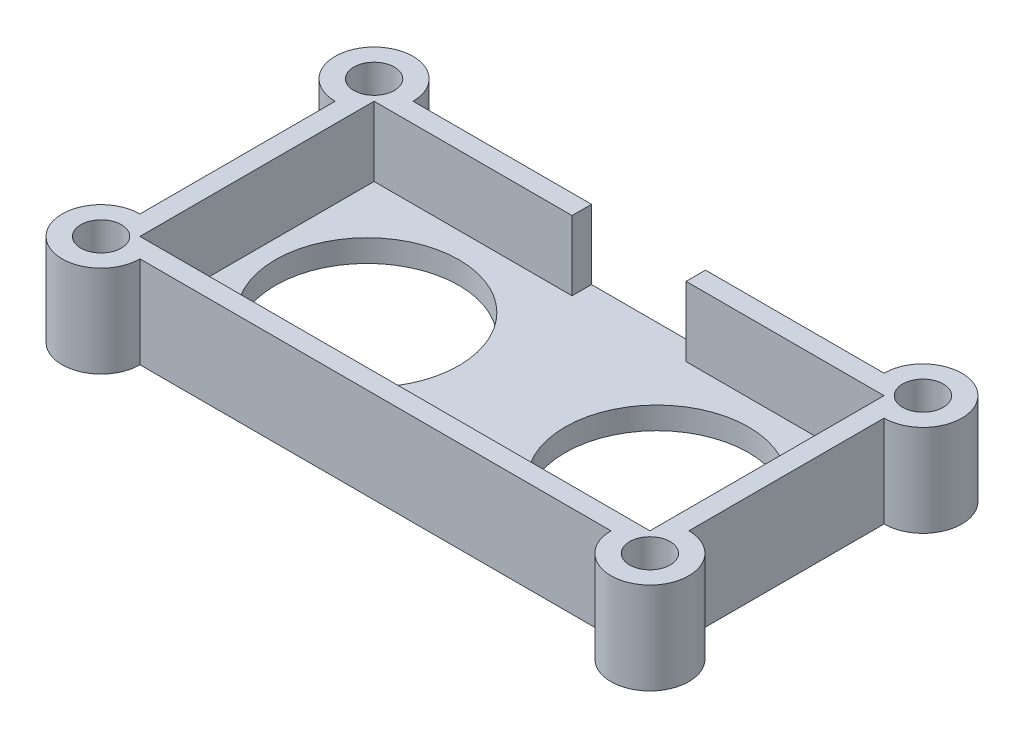
SolidWorks part; units mm, degrees
ref_plane "Front Plane" through (0, 0, 0) normal (0, 0, 1) x (1, 0, 0)
ref_plane "Top Plane" through (0, 0, 0) normal (0, 1, 0) x (1, 0, 0)
ref_plane "Right Plane" through (0, 0, 0) normal (1, 0, 0) x (0, 0, -1)
sketch "Sketch1" plane through (0, 0, 0) normal (0, 1, 0) x (1, 0, 0)
  line L1 (-24.675, 12.275) -> (24.675, 12.275)
  line L2 (-24.675, 12.275) -> (-24.675, -12.275)
  line L3 (-24.675, -12.275) -> (24.675, -12.275)
  line L4 (24.675, 12.275) -> (24.675, -12.275)
  dimension "D1" = 49.35
  dimension "D2" = 24.675
  dimension "D3" = 24.55
  dimension "D4" = 12.275
extrude "Boss-Extrude1" add sketch "Sketch1" along normal blind 2
sketch "Sketch2" plane through (0, 2, 0) normal (0, 1, 0) x (1, 0, 0)
  line L0 (-24.675, 12.275) -> (-24.675, -12.275)
  line L1 (-24.675, -12.275) -> (24.675, -12.275)
  line L2 (24.675, -12.275) -> (24.675, 12.275)
  line L3 (24.675, 12.275) -> (5.125, 12.275)
  line L4 (24.675, 12.275) -> (-24.675, 12.275) construction
  line L5 (5.125, 12.275) -> (5.125, 10.525)
  line L6 (5.125, 10.525) -> (22.925, 10.525)
  line L7 (22.925, 10.525) -> (22.925, -10.525)
  line L8 (22.925, -10.525) -> (-22.925, -10.525)
  line L9 (-22.925, -10.525) -> (-22.925, 10.525)
  line L10 (-22.925, 10.525) -> (-5.125, 10.525)
  line L11 (-5.125, 10.525) -> (-5.125, 12.275)
  line L12 (-5.125, 12.275) -> (-24.675, 12.275)
  dimension "D1" = 19.55
  dimension "D2" = 1.75
  dimension "D3" = 1.75
  dimension "D4" = 1.75
  dimension "D5" = 1.75
  dimension "D6" = 1.75
  dimension "D7" = 19.55
extrude "Boss-Extrude2" add sketch "Sketch2" along normal blind 6.25
sketch "Sketch4" plane through (0, 2, 0) normal (0, 1, 0) x (1, 0, 0)
  line L0 (-24.675, 12.275) -> (-24.675, 8.775)
  line L1 (-24.675, 12.275) -> (-21.175, 12.275)
  line L2 (-24.675, -12.275) -> (-24.675, -8.775)
  line L3 (-24.675, -12.275) -> (-21.175, -12.275)
  line L4 (24.675, -12.275) -> (21.175, -12.275)
  line L5 (24.675, -12.275) -> (24.675, -8.775)
  line L6 (24.675, 8.775) -> (24.675, 12.275)
  line L7 (24.675, 12.275) -> (21.175, 12.275)
  arc A0 (-21.175, 12.275) -> (-24.675, 8.775) centre (-24.675, 12.275) ccw
  arc A1 (-24.675, -8.775) -> (-21.175, -12.275) centre (-24.675, -12.275) ccw
  arc A2 (21.175, -12.275) -> (24.675, -8.775) centre (24.675, -12.275) ccw
  arc A3 (24.675, 8.775) -> (21.175, 12.275) centre (24.675, 12.275) ccw
  dimension "D1" = 7
  dimension "D2" = 7
  dimension "D3" = 7
  dimension "D4" = 7
extrude "Boss-Extrude3" add sketch "Sketch4" along normal up to surface and the other way up to surface
sketch "Sketch3" plane through (0, 2, 0) normal (0, 1, 0) x (1, 0, 0)
  line L0 (-3, -7.35) -> (3.25, -7.35) construction
  line L1 (-3, -4.975) -> (3.25, -4.975)
  line L2 (-3, -9.725) -> (3.25, -9.725)
  line L5 (-22.925, -10.525) -> (-22.925, 10.525) construction
  line L7 (22.925, 10.525) -> (22.925, -10.525) construction
  line L9 (22.925, -10.525) -> (-22.925, -10.525) construction
  line L11 (22.925, -10.525) -> (-22.925, -10.525) construction
  line L12 (-22.925, -10.525) -> (-22.925, 10.525) construction
  circle A0 centre (-13.025, 0) radius 8.25
  circle A1 centre (13.025, 0) radius 8.25
  arc A2 (-3, -4.975) -> (-3, -9.725) centre (-3, -7.35) ccw
  arc A3 (3.25, -9.725) -> (3.25, -4.975) centre (3.25, -7.35) ccw
  circle A4 centre (-24.675, 12.275) radius 1.825
  circle A5 centre (-24.675, -12.275) radius 1.825
  circle A6 centre (24.675, 12.275) radius 1.825
  circle A7 centre (24.675, -12.275) radius 1.825
  point P6 (0.125, -7.35)
  point P16 (-22.925, 0)
  point P18 (22.925, 0)
  point P23 (-5.375, -7.35)
  point P24 (5.625, -7.35)
  dimension "D1" = 16.5
  dimension "D2" = 16.5
  dimension "D11" = 3.65
  dimension "D12" = 3.65
  dimension "D13" = 3.65
  dimension "D14" = 3.65
  dimension "D3" = 9.9
  dimension "D4" = 9.9
  dimension "D5" = 10.525
  dimension "D6" = 10.525
  dimension "D7" = 4.75
  dimension "D8" = 0.8
  dimension "D9" = 11
  dimension "D10" = 17.55
extrude "Cut-Extrude1" cut sketch "Sketch3" against normal through all and the other way through all
